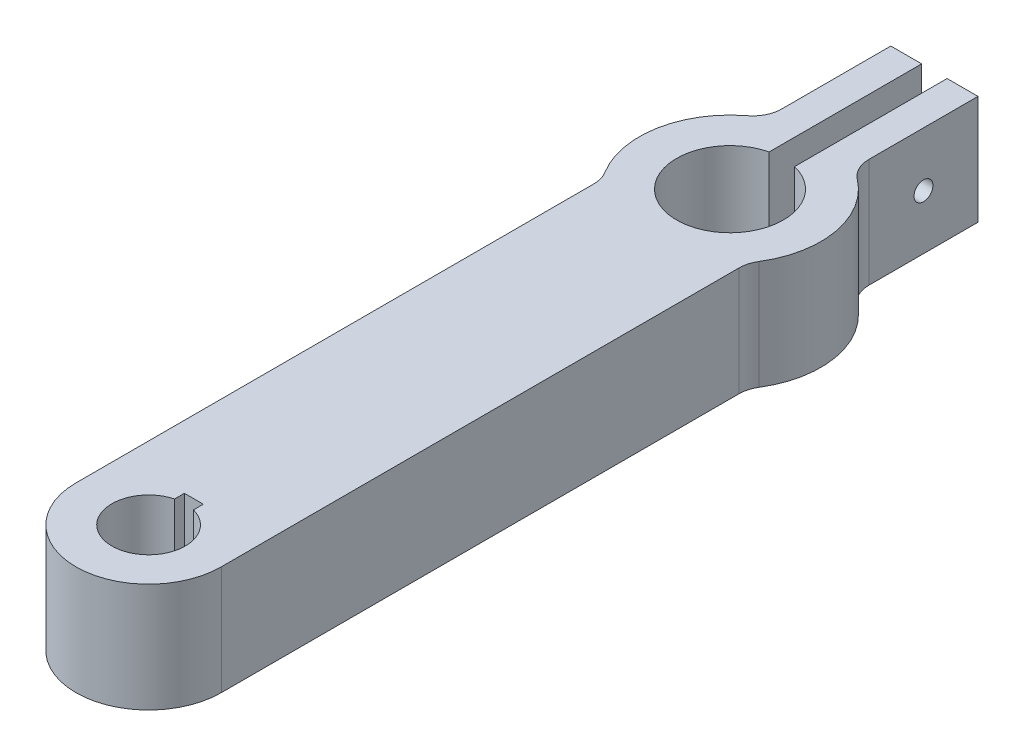
SolidWorks part; units mm, degrees
ref_plane "Front Plane" through (0, 0, 0) normal (0, 0, 1) x (1, 0, 0)
ref_plane "Top Plane" through (0, 0, 0) normal (0, 1, 0) x (1, 0, 0)
ref_plane "Right Plane" through (0, 0, 0) normal (1, 0, 0) x (0, 0, -1)
sketch "Sketch2" plane through (0, 0, 0) normal (0, 1, 0) x (1, 0, 0)
  line L0 (-25.4, 0) -> (-25.4, 181.0204)
  line L1 (25.4, 0) -> (25.4, 181.0204)
  line L2 (-4.445, 274.636) -> (-15.24, 274.636)
  line L3 (-15.24, 274.636) -> (-15.24, 236.536)
  line L4 (-4.445, 274.636) -> (-4.445, 221.3321)
  line L5 (0, 203.2) -> (0, 215.9) construction
  line L6 (4.445, 274.636) -> (4.445, 221.3321)
  line L7 (15.24, 274.636) -> (15.24, 236.536)
  line L8 (4.445, 274.636) -> (15.24, 274.636)
  circle A0 centre (0, 0) radius 12.827
  arc A1 (-25.4, 0) -> (25.4, 0) centre (0, 0) ccw
  arc A2 (-4.445, 221.3321) -> (4.445, 221.3321) centre (0, 203.2) ccw
  arc A3 (26.9394, 186.3973) -> (19.2424, 228.4545) centre (0, 203.2) ccw
  arc A4 (25.4, 181.0204) -> (26.9394, 186.3973) centre (35.56, 181.0204) cw
  arc A5 (-25.4, 181.0204) -> (-26.9394, 186.3973) centre (-35.56, 181.0204) ccw
  arc A6 (-19.2424, 228.4545) -> (-26.9394, 186.3973) centre (0, 203.2) ccw
  arc A8 (15.24, 236.536) -> (19.2424, 228.4545) centre (25.4, 236.536) ccw
  arc A9 (-15.24, 236.536) -> (-19.2424, 228.4545) centre (-25.4, 236.536) cw
  point P23 (15.24, 231.0533)
  point P26 (-15.24, 231.0533)
  dimension "D1" = 25.654
  dimension "D2" = 50.8
  dimension "D3" = 37.338
  dimension "D5" = 63.5
  dimension "D6" = 10.16
  dimension "D8" = 10.16
  dimension "D4" = 203.2
  dimension "D7" = 8.89
  dimension "D9" = 12.7
  dimension "D10" = 38.1
  dimension "D11" = 15.24
extrude "Boss-Extrude1" add sketch "Sketch2" along normal blind 38.1
sketch "Sketch3" plane through (-15.24, 0, 0) normal (-1, 0, 0) x (0, 0, 1)
  line L0 (-255.586, 38.1) -> (-255.586, 0) construction
  line L1 (-274.636, 38.1) -> (-236.536, 38.1) construction
  line L2 (-274.636, 0) -> (-236.536, 0) construction
  circle A0 centre (-255.586, 19.05) radius 3.302
  dimension "D1" = 6.604
extrude "Cut-Extrude1" cut sketch "Sketch3" against normal up to surface (30.48 mm away) up to face at (15.24, 19.05, -255.586)
sketch "Sketch4" plane through (0, 0, 0) normal (0, -1, 0) x (1, 0, 0)
  line L1 (-11.557, -85.725) -> (11.557, -85.725)
  line L2 (-11.557, -85.725) -> (-11.557, -117.475)
  line L3 (-11.557, -117.475) -> (11.557, -117.475)
  line L4 (11.557, -85.725) -> (11.557, -117.475)
  point P4 (0, -85.725)
  point P6 (11.557, -101.6)
  dimension "D1" = 23.114
  dimension "D2" = 31.75
  dimension "D3" = 101.6
extrude "Cut-Extrude2" cut sketch "Sketch4" against normal blind 5.08
sketch "Sketch5" plane through (0, 0, 0) normal (0, -1, 0) x (1, 0, 0)
  line L0 (11.557, -85.725) -> (-11.557, -85.725) construction
  line L1 (4.7625, -85.725) -> (-4.7625, -85.725)
  line L2 (4.7625, -85.725) -> (4.7625, -47.625)
  line L3 (4.7625, -47.625) -> (-4.7625, -47.625)
  line L4 (-4.7625, -85.725) -> (-4.7625, -47.625)
  line L5 (11.557, -85.725) -> (-11.557, -85.725) construction
  point P6 (0, -47.625)
  point P7 (0, -85.725)
  point P11 (0, -85.725)
  dimension "D1" = 9.525
  dimension "D2" = 38.1
extrude "Cut-Extrude3" cut sketch "Sketch5" against normal blind 5.08
sketch "Sketch6" plane through (0, 0, 0) normal (0, -1, 0) x (1, 0, 0)
  line L1 (3.302, -15.8237) -> (-3.302, -15.8237)
  line L2 (3.302, -15.8237) -> (3.302, -12.3947)
  line L3 (3.302, -12.3947) -> (-3.302, -12.3947)
  line L4 (-3.302, -15.8237) -> (-3.302, -12.3947)
  circle A0 centre (0, 0) radius 12.827 construction
  point P6 (0, -12.3947)
  dimension "D1" = 6.604
  dimension "D2" = 3.429
extrude "Cut-Extrude4" cut sketch "Sketch6" against normal up to next
